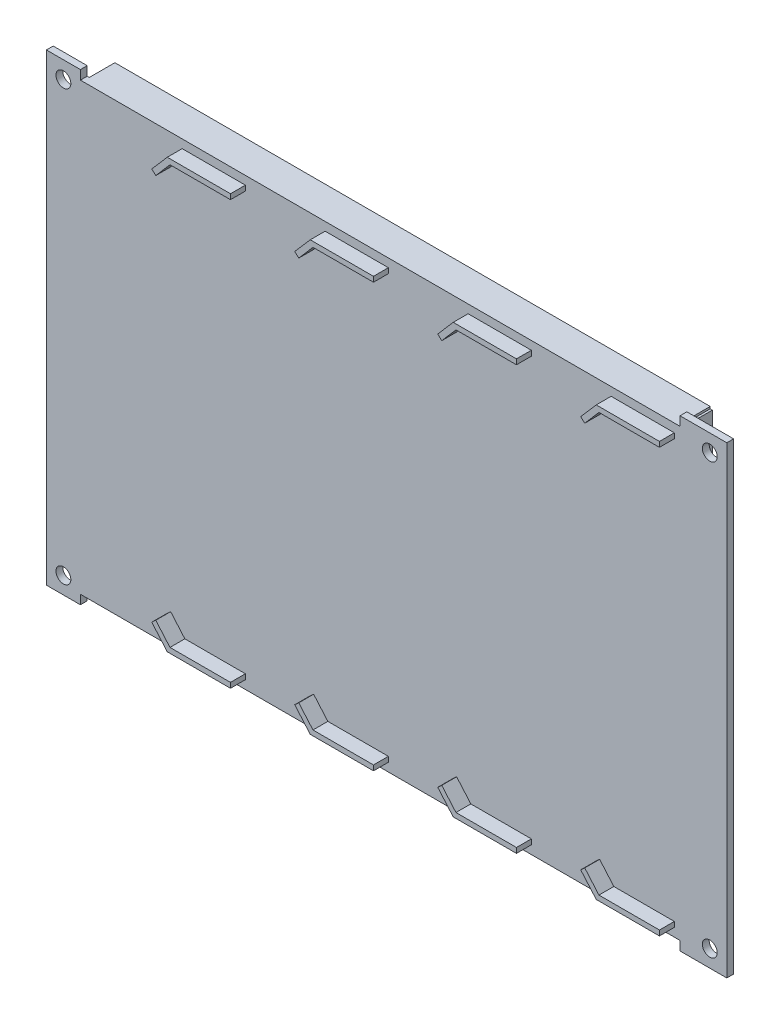
SolidWorks part; units mm, degrees
ref_plane "前视基准面" through (0, 0, 0) normal (0, 0, 1) x (1, 0, 0)
ref_plane "上视基准面" through (0, 0, 0) normal (0, 1, 0) x (1, 0, 0)
ref_plane "右视基准面" through (0, 0, 0) normal (1, 0, 0) x (0, 0, -1)
sketch "草图1" plane through (0, 0, 0) normal (0, 0, 1) x (1, 0, 0)
  line L0 (-82.6229, 0) -> (92.9476, 0) construction
  line L1 (0, 59.3874) -> (0, -61.8176) construction
  line L2 (-80, 54.5) -> (80, 54.5)
  line L7 (80, 54.5) -> (80, -54.5)
  line L8 (-80, -54.5) -> (80, -54.5)
  line L9 (-80, 54.5) -> (-80, -54.5)
  dimension "D1" = 160
  dimension "D2" = 109
extrude "拉伸1" add sketch "草图1" along normal blind 1.6
sketch "草图2" plane through (0, 0, 0) normal (0, 0, -1) x (-1, 0, 0)
  line L1 (-80, -54.5) -> (-80, 54.5) construction
  line L6 (-96.6133, 0) -> (105.2543, 0) construction
  circle A0 centre (-76, 50.5) radius 1.75
  circle A1 centre (76, 50.5) radius 1.75
  circle A2 centre (76, -50.5) radius 1.75
  circle A3 centre (-76, -50.5) radius 1.75
  dimension "D1" = 3.5
  dimension "D3" = 3.5
  dimension "D4" = 152
  dimension "D2" = 4
  dimension "D5" = 101
  dimension "D6" = 101
extrude "切除-拉伸1" cut sketch "草图2" against normal blind 2
sketch "草图4" plane through (0, 0, 0) normal (0, 0, -1) x (-1, 0, 0)
  line L0 (-80, -54.5) -> (-80, 54.5) construction
  line L1 (-69, 52.35) -> (72, 52.35)
  line L2 (-69, 52.35) -> (-69, -52.35)
  line L3 (-69, -52.35) -> (72, -52.35)
  line L4 (72, 52.35) -> (72, -52.35)
  line L5 (-90.4398, 0) -> (94.0653, 0) construction
  dimension "D1" = 104.7
  dimension "D2" = 141
  dimension "D3" = 11
extrude "拉伸2" add sketch "草图4" along normal blind 6
sketch "草图13" plane through (0, 0, 0) normal (0, 0, -1) x (-1, 0, 0)
  line L0 (-80, 54.5) -> (80, 54.5) construction
  line L1 (-69, 52.35) -> (72, 52.35)
  line L2 (-69, 52.35) -> (-69, 54.5)
  line L3 (-69, 54.5) -> (72, 54.5)
  line L4 (72, 52.35) -> (72, 54.5)
  line L5 (72, -52.35) -> (72, 52.35) construction
  line L6 (-95.192, 0) -> (106.118, 0) construction
  line L7 (72, -52.35) -> (72, -54.5)
  line L8 (-69, -54.5) -> (72, -54.5)
  line L9 (-69, -52.35) -> (-69, -54.5)
  line L10 (-69, -52.35) -> (72, -52.35)
extrude "切除-拉伸4" cut sketch "草图13" against normal blind 10
sketch "草图5" plane through (0, 0, -6) normal (0, 0, -1) x (-1, 0, 0)
  line L0 (-95.9126, 0) -> (91.592, 0) construction
  line L1 (-54.5, 45.95) -> (66.5, 45.95)
  line L2 (-55, 45.45) -> (-55, -45.55)
  line L3 (-54.5, -46.05) -> (66.5, -46.05)
  line L4 (67, 45.45) -> (67, -45.55)
  line L6 (-69, 52.35) -> (-69, -52.35) construction
  arc A0 (-55, 45.45) -> (-54.5, 45.95) centre (-54.5, 45.45) cw
  arc A1 (67, 45.45) -> (66.5, 45.95) centre (66.5, 45.45) ccw
  arc A2 (66.5, -46.05) -> (67, -45.55) centre (66.5, -45.55) ccw
  arc A3 (-54.5, -46.05) -> (-55, -45.55) centre (-54.5, -45.55) cw
  circle A7 centre (-76, 50.5) radius 1.75 construction
  point P10 (-55, 45.95)
  point P17 (-55, -46.05)
  dimension "D4" = 0.5
  dimension "D5" = 0.5
  dimension "D6" = 4.55
  dimension "D1" = 92
  dimension "D2" = 14
  dimension "D3" = 122
extrude "切除-拉伸2" cut sketch "草图5" against normal blind 1
sketch "草图6" plane through (0, 0, -6) normal (0, 0, -1) x (-1, 0, 0)
  line L0 (72, 52.35) -> (-69, 52.35) construction
  line L1 (71.5, 52.35) -> (72, 52.35)
  line L2 (71.5, 52.35) -> (71.5, 51.85)
  line L3 (71.5, 51.85) -> (72, 51.85)
  line L4 (72, 52.35) -> (72, 51.85)
  line L5 (72, -52.35) -> (72, 52.35) construction
  line L6 (-88.6383, 0) -> (99.8335, 0) construction
  line L7 (72, -52.35) -> (72, -51.85)
  line L8 (71.5, -51.85) -> (72, -51.85)
  line L9 (71.5, -52.35) -> (71.5, -51.85)
  line L10 (71.5, -52.35) -> (72, -52.35)
  line L11 (1.5, 52.35) -> (1.5, -52.35) construction
  line L12 (-69, -52.35) -> (72, -52.35) construction
  line L13 (-68.5, -52.35) -> (-69, -52.35)
  line L14 (-68.5, -52.35) -> (-68.5, -51.85)
  line L15 (-68.5, -51.85) -> (-69, -51.85)
  line L16 (-69, -52.35) -> (-69, -51.85)
  line L17 (-69, 52.35) -> (-69, 51.85)
  line L18 (-68.5, 51.85) -> (-69, 51.85)
  line L19 (-68.5, 52.35) -> (-68.5, 51.85)
  line L20 (-68.5, 52.35) -> (-69, 52.35)
  dimension "D1" = 0.5
  dimension "D2" = 0.5
extrude "切除-拉伸3" cut sketch "草图6" against normal up to surface (6 mm away) up to face at (-74.25, -50.5, 0)
sketch "草图10" plane through (0, 0, 1.6) normal (0, 0, 1) x (1, 0, 0)
  line L0 (89.2653, 0) -> (-84.9566, 0) construction
  line L1 (67.6629, -50.3588) -> (52.7937, -50.3588)
  line L2 (52.7937, -50.3588) -> (49.1466, -46.1506)
  line L3 (67.6629, -49.1475) -> (53.4306, -49.1475)
  line L4 (53.4306, -49.1475) -> (50.0943, -45.2804)
  line L5 (50.0943, -45.2804) -> (49.1466, -46.1506)
  line L6 (67.6629, -50.3588) -> (67.6629, -49.1475)
  line L7 (34.0389, -50.3588) -> (19.1697, -50.3588)
  line L8 (34.0389, -50.3588) -> (34.0389, -49.1475)
  line L9 (19.1697, -50.3588) -> (15.5226, -46.1506)
  line L10 (34.0389, -49.1475) -> (19.8066, -49.1475)
  line L11 (19.8066, -49.1475) -> (16.4703, -45.2804)
  line L12 (16.4703, -45.2804) -> (15.5226, -46.1506)
  line L13 (0.4149, -50.3588) -> (-14.4543, -50.3588)
  line L14 (0.4149, -50.3588) -> (0.4149, -49.1475)
  line L15 (-14.4543, -50.3588) -> (-18.1015, -46.1506)
  line L16 (0.4149, -49.1475) -> (-13.8174, -49.1475)
  line L17 (-13.8174, -49.1475) -> (-17.1538, -45.2804)
  line L18 (-17.1538, -45.2804) -> (-18.1015, -46.1506)
  line L19 (-33.2092, -50.3588) -> (-48.0783, -50.3588)
  line L20 (-33.2092, -50.3588) -> (-33.2092, -49.1475)
  line L21 (-48.0783, -50.3588) -> (-51.7255, -46.1506)
  line L22 (-33.2092, -49.1475) -> (-47.4415, -49.1475)
  line L23 (-47.4415, -49.1475) -> (-50.7778, -45.2804)
  line L24 (-50.7778, -45.2804) -> (-51.7255, -46.1506)
  line L25 (-50.7778, 45.2804) -> (-51.7255, 46.1506)
  line L26 (-47.4415, 49.1475) -> (-50.7778, 45.2804)
  line L27 (-33.2092, 49.1475) -> (-47.4415, 49.1475)
  line L28 (-48.0783, 50.3588) -> (-51.7255, 46.1506)
  line L29 (-33.2092, 50.3588) -> (-33.2092, 49.1475)
  line L30 (-33.2092, 50.3588) -> (-48.0783, 50.3588)
  line L31 (-17.1538, 45.2804) -> (-18.1015, 46.1506)
  line L32 (-13.8174, 49.1475) -> (-17.1538, 45.2804)
  line L33 (0.4149, 49.1475) -> (-13.8174, 49.1475)
  line L34 (-14.4543, 50.3588) -> (-18.1015, 46.1506)
  line L35 (0.4149, 50.3588) -> (0.4149, 49.1475)
  line L36 (0.4149, 50.3588) -> (-14.4543, 50.3588)
  line L37 (16.4703, 45.2804) -> (15.5226, 46.1506)
  line L38 (19.8066, 49.1475) -> (16.4703, 45.2804)
  line L39 (34.0389, 49.1475) -> (19.8066, 49.1475)
  line L40 (19.1697, 50.3588) -> (15.5226, 46.1506)
  line L41 (34.0389, 50.3588) -> (34.0389, 49.1475)
  line L42 (34.0389, 50.3588) -> (19.1697, 50.3588)
  line L43 (67.6629, 50.3588) -> (67.6629, 49.1475)
  line L44 (50.0943, 45.2804) -> (49.1466, 46.1506)
  line L45 (53.4306, 49.1475) -> (50.0943, 45.2804)
  line L46 (67.6629, 49.1475) -> (53.4306, 49.1475)
  line L47 (52.7937, 50.3588) -> (49.1466, 46.1506)
  line L48 (67.6629, 50.3588) -> (52.7937, 50.3588)
extrude "拉伸5" add sketch "草图10" along normal blind 3.5
sketch "草图12" plane through (0, 0, 0) normal (0, 0, -1) x (-1, 0, 0)
  line L0 (79.4, 40) -> (79.4, -40)
  line L1 (-88.6195, 0) -> (85.9769, 0) construction
  line L2 (79.4, 40) -> (72, 45.5)
  line L3 (72, -51.85) -> (72, 51.85) construction
  line L4 (79.4, -40) -> (72, -45.5)
  line L5 (72, 45.5) -> (72, -45.5)
  dimension "D1" = 80
  dimension "D2" = 91
  dimension "D3" = 7.4
extrude "拉伸6" add sketch "草图12" along normal blind 3.5
